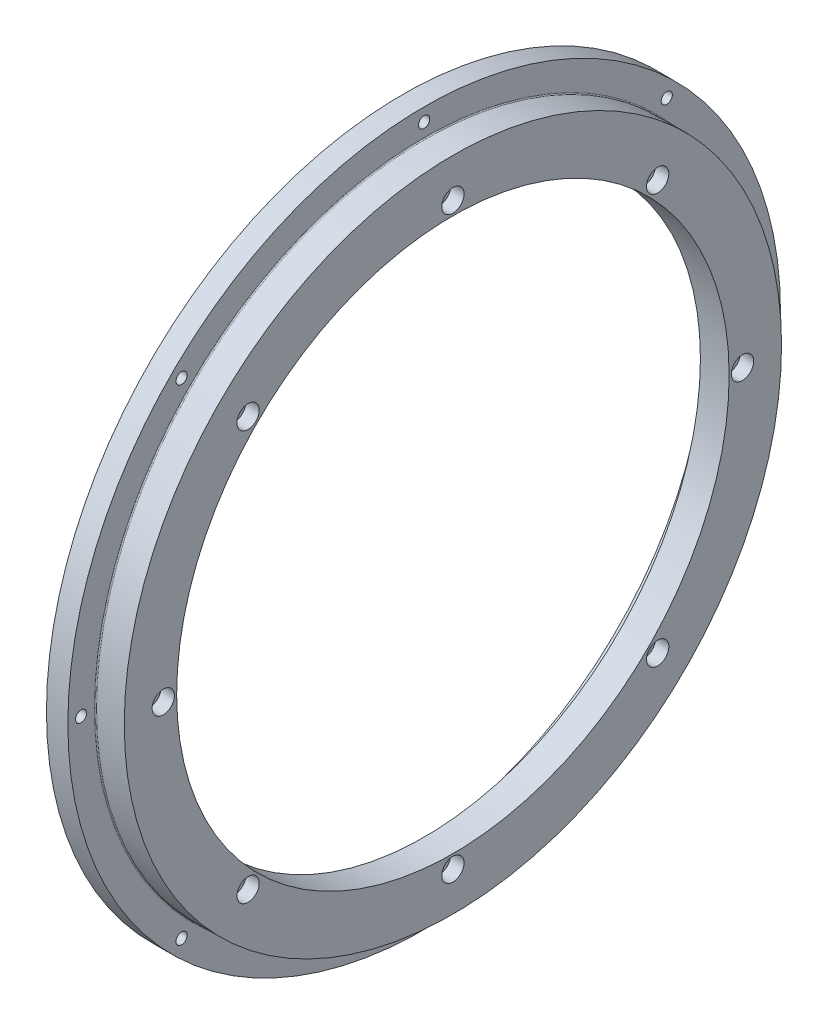
SolidWorks part; units mm, degrees
ref_plane "Front Plane" through (0, 0, 0) normal (0, 0, 1) x (1, 0, 0)
ref_plane "Top Plane" through (0, 0, 0) normal (0, 1, 0) x (1, 0, 0)
ref_plane "Right Plane" through (0, 0, 0) normal (1, 0, 0) x (0, 0, -1)
sketch "Sketch1" plane through (0, 0, 0) normal (0, 1, 0) x (1, 0, 0)
  line L0 (-17.8562, 253.9111) -> (-2.6162, 253.9111)
  line L1 (-2.6162, 253.9111) -> (-2.6162, 234.188)
  line L2 (-2.6162, 234.188) -> (17.8562, 234.188)
  line L3 (17.8562, 234.188) -> (17.8562, 196.85)
  line L4 (17.8562, 196.85) -> (-2.6162, 196.85)
  line L5 (-2.6162, 196.85) -> (-2.6162, 215.9127)
  line L6 (-2.6162, 215.9127) -> (-17.8562, 215.9127)
  line L7 (-17.8562, 215.9127) -> (-17.8562, 253.9111)
  line L8 (-43.2562, 0) -> (43.2562, 0) construction
  point P10 (0, 0)
  dimension "D1" = 20.4724
  dimension "D2" = 35.7124
  dimension "D3" = 19.7231
  dimension "D4" = 37.9984
  dimension "D5" = 57.0611
  dimension "D6" = 253.9111
  dimension "D7" = 17.8562
revolve "Revolve1" add sketch "Sketch1" angle 360 about L8
fillet "Fillet1" radius 0.762 1 edges at (-2.6162, 0, 234.188)
fillet "Fillet2" radius 0.762 1 edges at (-2.6162, 0, 215.9127)
sketch "Sketch2" plane through (0, 0, 0) normal (1, 0, 0) x (0, 0, -1)
  circle A0 centre (244.475, 0) radius 3.9687
  circle A1 centre (172.8699, 172.8699) radius 3.9687
  circle A2 centre (0, 244.475) radius 3.9688
  circle A3 centre (-172.8699, 172.8699) radius 3.9687
  circle A4 centre (-244.475, 0) radius 3.9687
  circle A5 centre (-172.8699, -172.8699) radius 3.9687
  circle A6 centre (0, -244.475) radius 3.9688
  circle A7 centre (172.8699, -172.8699) radius 3.9687
  point P16 (0, 0)
  dimension "D1" = 7.9375
  dimension "D2" = 7.9375
  dimension "D3" = 7.9375
  dimension "D4" = 7.9375
  dimension "D5" = 7.9375
  dimension "D6" = 7.9375
  dimension "D7" = 7.9375
  dimension "D8" = 7.9375
  dimension "D9" = 71.6051
  dimension "D10" = 244.475
  dimension "D11" = 417.3449
  dimension "D12" = 488.95
  dimension "D13" = 71.6051
  dimension "D14" = 244.475
  dimension "D15" = 417.3449
  dimension "D16" = 488.95
extrude "Cut-Extrude2" cut sketch "Sketch2" along normal blind 35.7124 from offset 17.8562
sketch "Sketch3" plane through (0, 0, 0) normal (1, 0, 0) x (0, 0, -1)
  circle A0 centre (206.375, 0) radius 5.1562
  circle A1 centre (145.9292, 145.9292) radius 5.1562
  circle A2 centre (0, 206.375) radius 5.1562
  circle A3 centre (-145.9292, 145.9292) radius 5.1562
  circle A4 centre (-206.375, 0) radius 5.1562
  circle A5 centre (-145.9292, -145.9292) radius 5.1562
  circle A6 centre (0, -206.375) radius 5.1562
  circle A7 centre (145.9292, -145.9292) radius 5.1562
  point P16 (0, 0)
  dimension "D1" = 10.3124
  dimension "D2" = 10.3124
  dimension "D3" = 10.3124
  dimension "D4" = 10.3124
  dimension "D5" = 10.3124
  dimension "D6" = 10.3124
  dimension "D7" = 10.3124
  dimension "D8" = 10.3124
  dimension "D9" = 60.4458
  dimension "D10" = 206.375
  dimension "D11" = 352.3042
  dimension "D12" = 412.75
  dimension "D13" = 60.4458
  dimension "D14" = 206.375
  dimension "D15" = 352.3042
  dimension "D16" = 412.75
extrude "Cut-Extrude4" cut sketch "Sketch3" against normal blind 35.7124 from offset 17.8562
sketch "Sketch4" plane through (0, 0, 0) normal (1, 0, 0) x (0, 0, -1)
  circle A0 centre (206.375, 0) radius 7.9375
  circle A1 centre (145.9292, 145.9292) radius 7.9375
  circle A2 centre (0, 206.375) radius 7.9375
  circle A3 centre (-145.9292, 145.9292) radius 7.9375
  circle A4 centre (-206.375, 0) radius 7.9375
  circle A5 centre (-145.9292, -145.9292) radius 7.9375
  circle A6 centre (0, -206.375) radius 7.9375
  circle A7 centre (145.9292, -145.9292) radius 7.9375
  point P16 (0, 0)
  dimension "D1" = 15.875
  dimension "D2" = 15.875
  dimension "D3" = 15.875
  dimension "D4" = 15.875
  dimension "D5" = 15.875
  dimension "D6" = 15.875
  dimension "D7" = 15.875
  dimension "D8" = 15.875
  dimension "D9" = 60.4458
  dimension "D10" = 206.375
  dimension "D11" = 352.3042
  dimension "D12" = 412.75
  dimension "D13" = 60.4458
  dimension "D14" = 206.375
  dimension "D15" = 352.3042
  dimension "D16" = 412.75
extrude "Cut-Extrude6" cut sketch "Sketch4" against normal blind 9.525 from offset 17.8562
